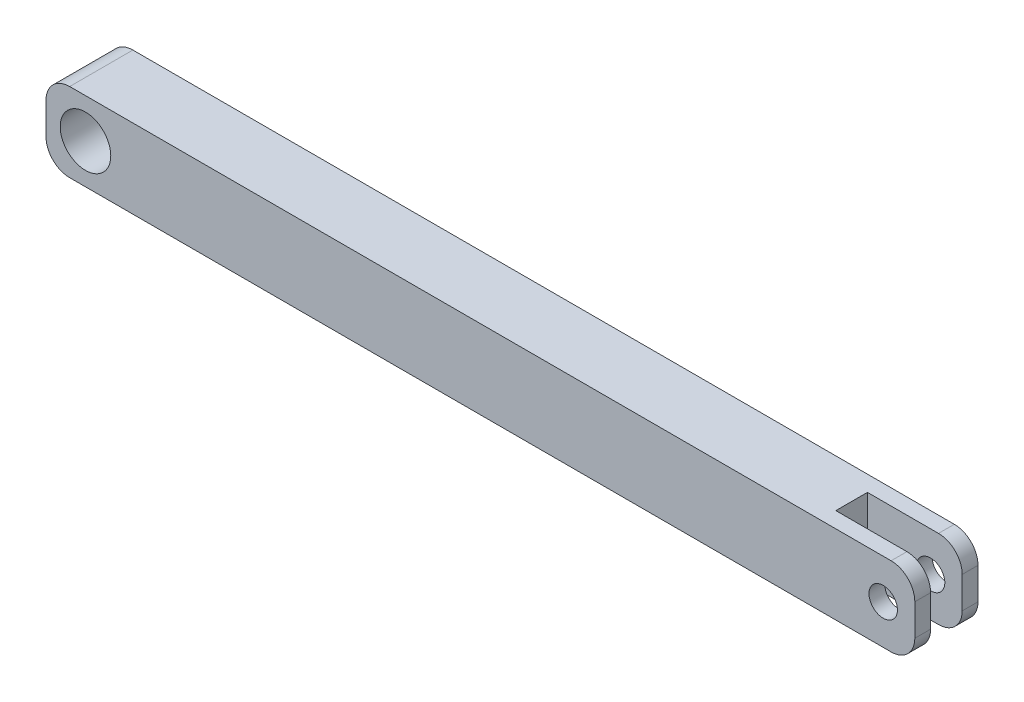
SolidWorks part; units mm, degrees
ref_plane "前视基准面" through (0, 0, 0) normal (0, 0, 1) x (1, 0, 0)
ref_plane "上视基准面" through (0, 0, 0) normal (0, 1, 0) x (1, 0, 0)
ref_plane "右视基准面" through (0, 0, 0) normal (1, 0, 0) x (0, 0, -1)
other "Configuration Table"
sketch "草图5" plane through (0, 0, 0) normal (0, 1, 0) x (1, 0, 0)
  line L0 (0, 0) -> (0, -3)
  line L4 (55, -3) -> (55, 0)
  line L8 (55, 0) -> (0, 0)
  line L9 (0, -3) -> (55, -3)
  dimension "D6" = 3
  dimension "D1" = 55
  dimension "D5" = 3
extrude "凸台-拉伸1" add sketch "草图5" along normal blind 5
sketch "草图6" plane through (0, 0, 3) normal (0, 0, 1) x (1, 0, 0)
  line L2 (0, 5) -> (0, 0) construction
  line L3 (0, 5) -> (55, 5) construction
  circle A0 centre (2.5, 2.5) radius 1.6
  dimension "D1" = 3.2
  dimension "D2" = 2.5
  dimension "D3" = 2.5
extrude "切除-拉伸1" cut sketch "草图6" against normal up to next
sketch "草图7" plane through (0, 0, 0) normal (0, 0, 1) x (1, 0, 0)
  line L0 (55, 5) -> (55, 0) construction
  circle A0 centre (53, 2.5) radius 0.9
  point P6 (55, 2.5)
  dimension "D1" = 1.8
  dimension "D2" = 2
extrude "切除-拉伸2" cut sketch "草图7" along normal up to next
fillet "圆角1" radius 1.5 4 edges at (55, 5, 1.5) (55, 0, 1.5) (0, 0, 1.5) (0, 5, 1.5)
sketch "草图8" plane through (0, 5, 0) normal (0, 1, 0) x (1, 0, 0)
  line L0 (55, 0) -> (55, -3) construction
  line L1 (55, -0.7) -> (49, -0.7)
  line L2 (55, -0.7) -> (55, -2.3)
  line L3 (55, -2.3) -> (49, -2.3)
  line L4 (49, -0.7) -> (49, -2.3)
  point P6 (55, -1.5)
  dimension "D1" = 1.6
  dimension "D2" = 6
extrude "切除-拉伸3" cut sketch "草图8" against normal blind 10
sketch "草图10" plane through (0, 0, 3) normal (0, 0, 1) x (1, 0, 0)
  line L3 (55, 1.5) -> (55, 3.5)
  line L6 (0, 3.5) -> (0, 1.5)
  line L10 (0, 3.5) -> (0, 1.5)
  line L18 (55, 1.5) -> (55, 3.5)
  line L23 (53.5, 5) -> (1.5, 5)
  line L24 (53.5, 5) -> (1.5, 5)
  line L25 (1.5, 0) -> (53.5, 0)
  line L26 (1.5, 0) -> (53.5, 0)
  circle A0 centre (2.5, 2.5) radius 1.6 construction
  circle A1 centre (2.5, 2.5) radius 1.6
  circle A2 centre (53, 2.5) radius 0.9 construction
  circle A3 centre (53, 2.5) radius 0.9
  arc A4 (55, 3.5) -> (53.5, 5) centre (53.5, 3.5) ccw
  arc A5 (1.5, 5) -> (0, 3.5) centre (1.5, 3.5) ccw
  arc A6 (0, 1.5) -> (1.5, 0) centre (1.5, 1.5) ccw
  arc A9 (1.5, 5) -> (0, 3.5) centre (1.5, 3.5) ccw
  arc A10 (0, 1.5) -> (1.5, 0) centre (1.5, 1.5) ccw
  arc A22 (55, 3.5) -> (53.5, 5) centre (53.5, 3.5) ccw
  arc A23 (53.5, 0) -> (55, 1.5) centre (53.5, 1.5) ccw
  arc A24 (53.5, 0) -> (55, 1.5) centre (53.5, 1.5) ccw
  dimension "D1" = 0
extrude "凸台-拉伸2" add sketch "草图10" along normal blind 0.5
sketch "草图11" plane through (0, 0, 0) normal (0, 0, -1) x (-1, 0, 0)
  line L3 (-1.5, 5) -> (-53.5, 5)
  line L5 (-1.5, 5) -> (-53.5, 5)
  line L7 (0, 1.5) -> (0, 3.5)
  line L11 (0, 1.5) -> (0, 3.5)
  line L13 (-55, 3.5) -> (-55, 1.5)
  line L14 (-55, 3.5) -> (-55, 1.5)
  line L15 (-53.5, 0) -> (-1.5, 0)
  line L16 (-53.5, 0) -> (-1.5, 0)
  circle A0 centre (-53, 2.5) radius 0.9 construction
  circle A1 centre (-2.5, 2.5) radius 1.6 construction
  circle A2 centre (-53, 2.5) radius 0.9
  circle A3 centre (-2.5, 2.5) radius 1.6
  arc A4 (-53.5, 5) -> (-55, 3.5) centre (-53.5, 3.5) ccw
  arc A6 (-1.5, 0) -> (0, 1.5) centre (-1.5, 1.5) ccw
  arc A7 (0, 3.5) -> (-1.5, 5) centre (-1.5, 3.5) ccw
  arc A10 (-1.5, 0) -> (0, 1.5) centre (-1.5, 1.5) ccw
  arc A11 (0, 3.5) -> (-1.5, 5) centre (-1.5, 3.5) ccw
  arc A16 (-53.5, 5) -> (-55, 3.5) centre (-53.5, 3.5) ccw
  arc A17 (-55, 1.5) -> (-53.5, 0) centre (-53.5, 1.5) ccw
  arc A18 (-55, 1.5) -> (-53.5, 0) centre (-53.5, 1.5) ccw
  dimension "D1" = 0
extrude "凸台-拉伸3" add sketch "草图11" along normal blind 0.5
sketch "草图12" plane through (0, 5, 0) normal (0, 1, 0) x (1, 0, 0)
  line L0 (53.5, -0.7) -> (49, -0.7) construction
  line L1 (55.9535, -2.5) -> (49, -2.5)
  line L2 (55.9535, -2.5) -> (55.9535, -0.5)
  line L3 (55.9535, -0.5) -> (49, -0.5)
  line L4 (49, -2.5) -> (49, -0.5)
  line L5 (55.9535, -2.5) -> (49, -0.5) construction
  line L6 (55.9535, -0.5) -> (49, -2.5) construction
  line L7 (49, -2.3) -> (53.5, -2.3) construction
  line L8 (55, 0.5) -> (55, -0.7) construction
  point P0 (52.4767, -1.5)
  dimension "D1" = 0.2
  dimension "D2" = 0.2
  dimension "D3" = 6
extrude "切除-拉伸4" cut sketch "草图12" against normal blind 10
